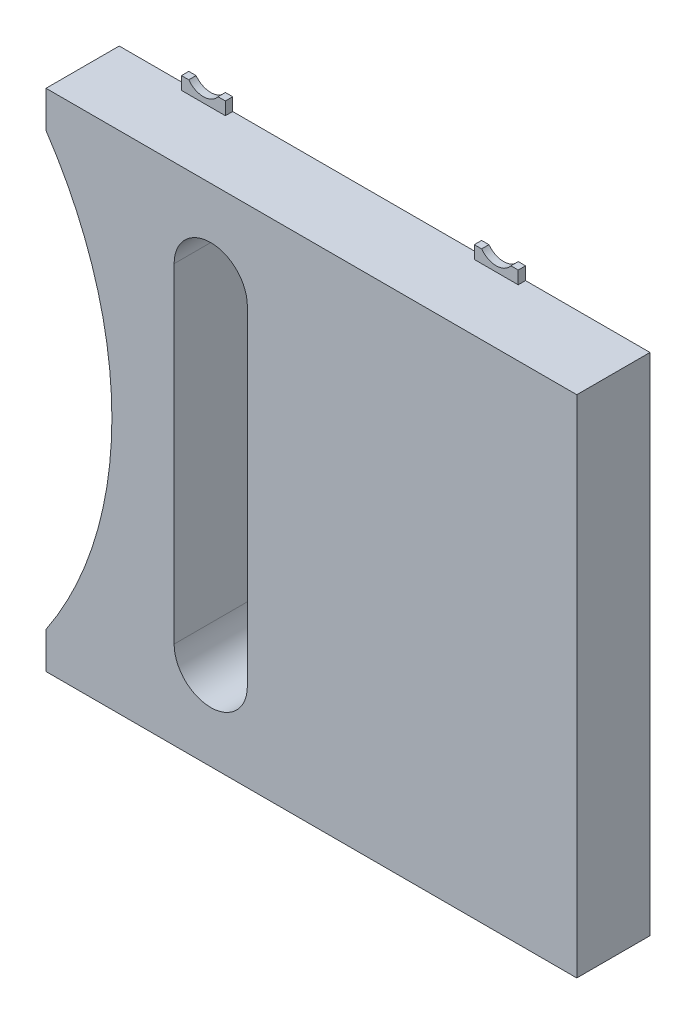
SolidWorks part; units mm, degrees
ref_plane "Front Plane" through (0, 0, 0) normal (0, 0, 1) x (1, 0, 0)
ref_plane "Top Plane" through (0, 0, 0) normal (0, 1, 0) x (1, 0, 0)
ref_plane "Right Plane" through (0, 0, 0) normal (1, 0, 0) x (0, 0, -1)
sketch "Sketch1" plane through (0, 0, 0) normal (0, 0, 1) x (1, 0, 0)
  line L0 (-7.25, 6.9) -> (-7.25, 5.9)
  line L1 (-7.25, 6.9) -> (7.25, 6.9)
  line L2 (-7.25, 6.9) -> (-7.25, -6.9) construction
  line L3 (-7.25, -6.9) -> (7.25, -6.9)
  line L4 (7.25, 6.9) -> (7.25, -6.9)
  line L5 (-7.25, 6.9) -> (7.25, -6.9) construction
  line L6 (-7.25, -6.9) -> (7.25, 6.9) construction
  line L7 (-7.25, -6.9) -> (-7.25, -5.9)
  line L8 (0, 0) -> (-16.0194, 0) construction
  line L9 (-5.45, 3.1871) -> (-5.45, -2.6032) construction
  line L10 (-2.75, -4.5) -> (-2.75, 4.5) construction
  line L11 (-3.75, -4.5) -> (-3.75, 4.5)
  line L12 (-1.75, -4.5) -> (-1.75, 4.5)
  arc A0 (-7.25, 5.9) -> (-7.25, -5.9) centre (-16.0194, 0) cw
  arc A1 (-3.75, -4.5) -> (-1.75, -4.5) centre (-2.75, -4.5) ccw
  arc A2 (-1.75, 4.5) -> (-3.75, 4.5) centre (-2.75, 4.5) ccw
  point P0 (0, 0)
  point P14 (-2.75, 0)
  dimension "D1" = 14.5
  dimension "D2" = 13.8
  dimension "D3" = 1
  dimension "D4" = 1.8
  dimension "D5" = 4.5
  dimension "D6" = 2
  dimension "D7" = 9
extrude "Boss-Extrude1" add sketch "Sketch1" along normal blind 2
sketch "Sketch2" plane through (0, 0, 0) normal (0, 0, 1) x (1, 0, 0)
  line L0 (-5.15, 7.25) -> (-5.35, 7.25)
  line L1 (-5.35, 7.25) -> (-5.35, 6.9)
  line L2 (7.25, 6.9) -> (-7.25, 6.9) construction
  line L3 (-5.35, 6.9) -> (-4.15, 6.9)
  line L4 (-4.15, 6.9) -> (-4.15, 7.25)
  line L5 (-4.15, 7.25) -> (-4.35, 7.25)
  line L6 (-7.25, 6.9) -> (-7.25, 5.9) construction
  line L7 (-0.75, 9.9896) -> (-0.75, 5.3135) construction
  line L8 (2.65, 7.25) -> (2.85, 7.25)
  line L9 (2.65, 6.9) -> (2.65, 7.25)
  line L10 (3.85, 6.9) -> (2.65, 6.9)
  line L11 (3.85, 7.25) -> (3.85, 6.9)
  line L12 (3.65, 7.25) -> (3.85, 7.25)
  line L13 (7.25, -6.9) -> (7.25, 6.9) construction
  line L14 (0, 0) -> (-10.2026, 0) construction
  line L15 (3.65, -7.25) -> (3.85, -7.25)
  line L16 (3.85, -7.25) -> (3.85, -6.9)
  line L17 (3.85, -6.9) -> (2.65, -6.9)
  line L18 (2.65, -6.9) -> (2.65, -7.25)
  line L19 (2.65, -7.25) -> (2.85, -7.25)
  line L20 (-4.15, -7.25) -> (-4.35, -7.25)
  line L21 (-4.15, -6.9) -> (-4.15, -7.25)
  line L22 (-5.35, -6.9) -> (-4.15, -6.9)
  line L23 (-5.35, -7.25) -> (-5.35, -6.9)
  line L24 (-5.15, -7.25) -> (-5.35, -7.25)
  arc A0 (-5.15, 7.25) -> (-4.35, 7.25) centre (-4.75, 7.55) ccw
  arc A1 (3.65, 7.25) -> (2.85, 7.25) centre (3.25, 7.55) cw
  arc A2 (3.65, -7.25) -> (2.85, -7.25) centre (3.25, -7.55) ccw
  arc A3 (-5.15, -7.25) -> (-4.35, -7.25) centre (-4.75, -7.55) cw
  point P8 (-4.75, 6.9)
  point P23 (3.25, 6.9)
  dimension "D6" = 0.5
  dimension "D1" = 0.2
  dimension "D2" = 1.2
  dimension "D3" = 2.5
  dimension "D4" = 4
  dimension "D5" = 14.5
extrude "Boss-Extrude2" add sketch "Sketch2" along normal blind 0.2
